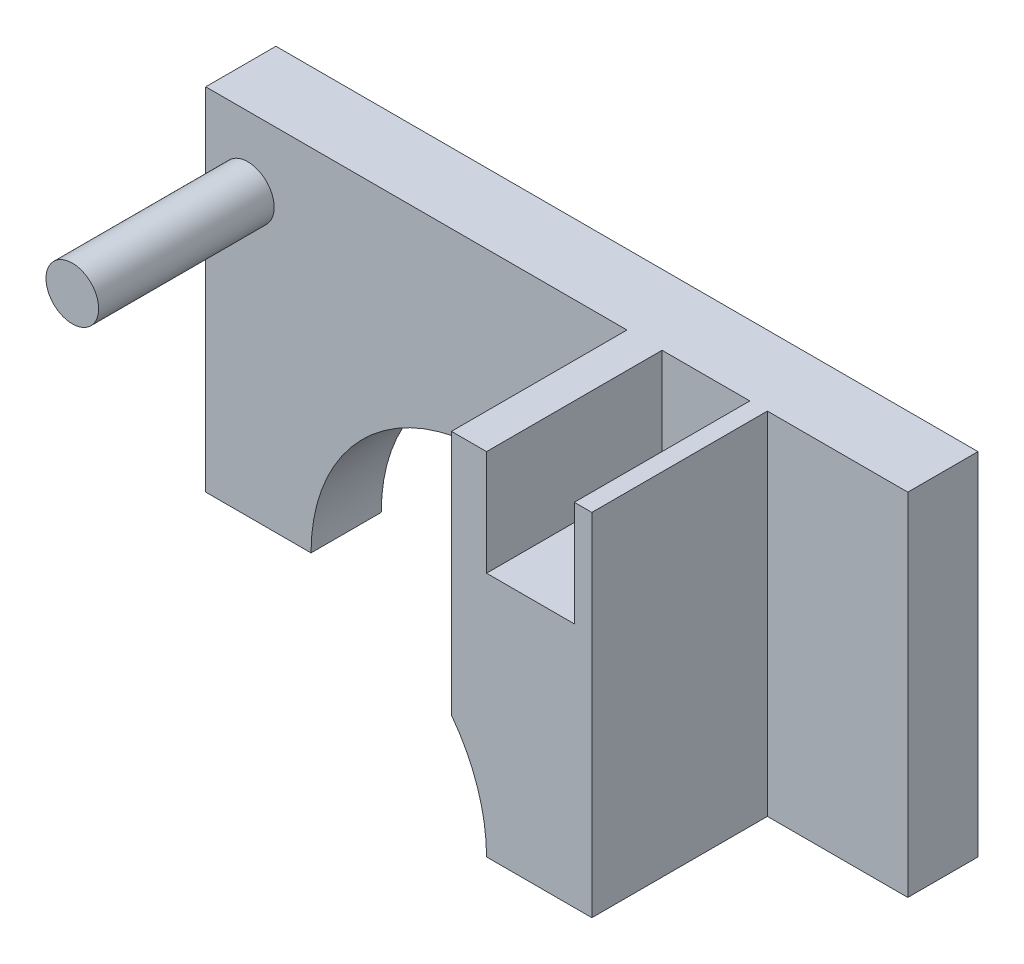
SolidWorks part; units mm, degrees
ref_plane "Přední rovina" through (0, 0, 0) normal (0, 0, 1) x (1, 0, 0)
ref_plane "Horní rovina" through (0, 0, 0) normal (0, 1, 0) x (1, 0, 0)
ref_plane "Pravá rovina" through (0, 0, 0) normal (1, 0, 0) x (0, 0, -1)
sketch "Skica1" plane through (0, 0, 0) normal (0, 0, 1) x (1, 0, 0)
  line L1 (0, 0) -> (200, 0)
  line L2 (0, 0) -> (0, 100)
  line L3 (0, 100) -> (200, 100)
  line L4 (200, 0) -> (200, 100)
  dimension "D1" = 100
  dimension "D2" = 200
extrude "Přidat vysunutím1" add sketch "Skica1" along normal blind 20
sketch "Skica2" plane through (0, 0, 20) normal (0, 0, 1) x (1, 0, 0)
  line L0 (0, 0) -> (200, 0) construction
  line L1 (120, 0) -> (160, 0)
  line L2 (120, 0) -> (120, 100)
  line L3 (120, 100) -> (130, 100)
  line L4 (160, 0) -> (160, 100)
  line L5 (200, 100) -> (0, 100) construction
  line L6 (0, 100) -> (0, 0) construction
  line L7 (155, 100) -> (160, 100)
  line L9 (130, 100) -> (130, 70)
  line L10 (130, 70) -> (155, 70)
  line L11 (155, 100) -> (155, 70)
  dimension "D1" = 120
  dimension "D2" = 40
  dimension "D3" = 10
  dimension "D4" = 5
  dimension "D5" = 30
extrude "Přidat vysunutím2" add sketch "Skica2" along normal blind 50 contours L9 L10 L11 L7 L4 L1 L2 L3
sketch "Skica4" plane through (0, 0, 0) normal (0, 0, -1) x (-1, 0, 0)
  line L0 (0, 0) -> (-200, 0) construction
  circle A0 centre (-80, 0) radius 50
  dimension "D1" = 100
  dimension "D2" = 80
extrude "Odebrat vysunutím1" cut sketch "Skica4" against normal up to surface (70 mm away) up to face at (141.25, 67.5, 70)
sketch "Skica7" plane through (0, 0, 20) normal (0, 0, 1) x (1, 0, 0)
  line L0 (120, 100) -> (0, 100) construction
  line L2 (0, 100) -> (0, 0) construction
  circle A0 centre (12, 80) radius 7.5
  dimension "D1" = 15
  dimension "D2" = 20
  dimension "D3" = 12
extrude "Přidat vysunutím3" add sketch "Skica7" along normal blind 50
